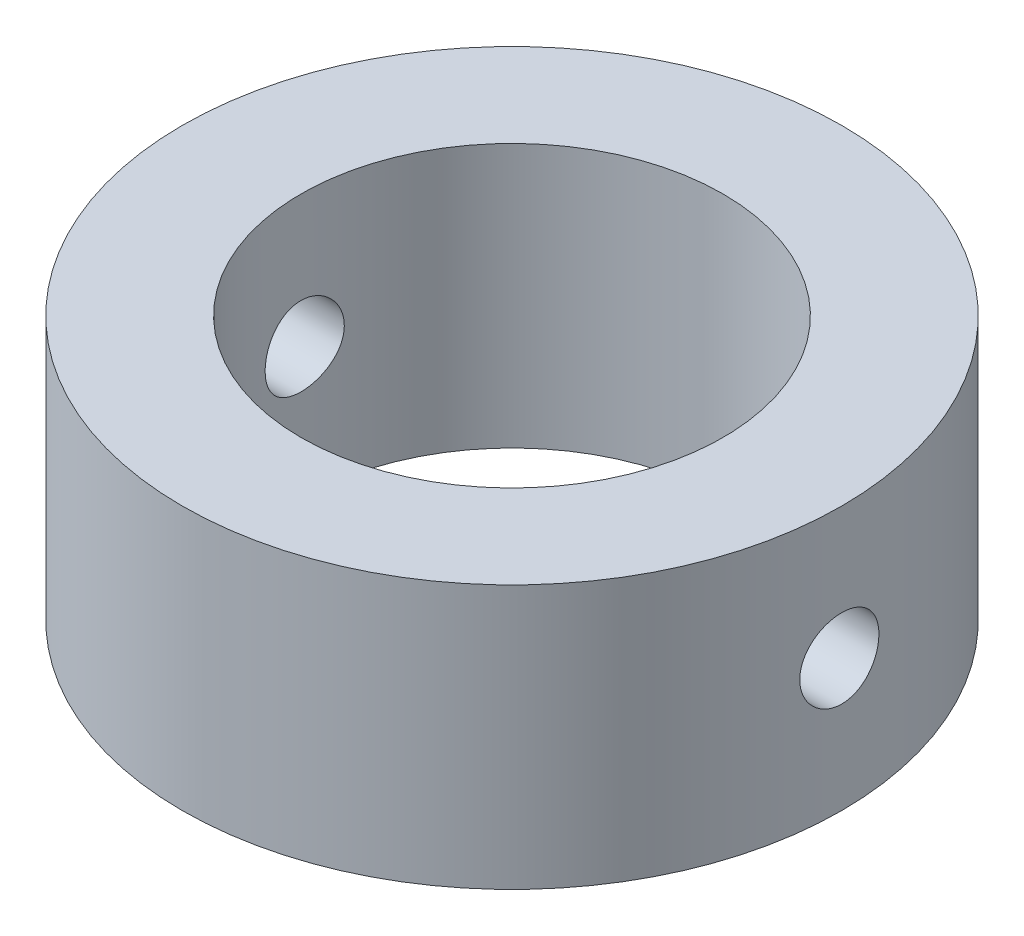
SolidWorks part; units mm, degrees
material "AISI 4130 Steel, normalized at 870C"
ref_plane "Front Plane" through (0, 0, 0) normal (0, 0, 1) x (1, 0, 0)
ref_plane "Top Plane" through (0, 0, 0) normal (0, 1, 0) x (1, 0, 0)
ref_plane "Right Plane" through (0, 0, 0) normal (1, 0, 0) x (0, 0, -1)
sketch "Sketch1" plane through (0, 0, 0) normal (0, 1, 0) x (1, 0, 0)
  circle A0 centre (0, 0) radius 12.5
  circle A1 centre (0, 0) radius 8
extrude "Boss-Extrude1" add sketch "Sketch1" along normal blind 10
sketch "Sketch2" plane through (0, 10, 0) normal (0, 1, 0) x (1, 0, 0)
  line L0 (0, 0) -> (-12.5, 0) construction
  circle A0 centre (0, 0) radius 12.5 construction
ref_plane "Plane1" through (-12.5, 0, 0) normal (-1, 0, 0) x (0, 0, 1)
sketch "Sketch3" plane through (-12.5, 0, 0) normal (-1, 0, 0) x (0, 0, 1)
  line L0 (8, 10) -> (-8, 10) construction
  line L1 (-12.5, 10) -> (-12.5, 0) construction
  circle A0 centre (0, 5) radius 1.5
  dimension "D1" = 5
  dimension "D2" = 12.5
extrude "Cut-Extrude1" cut sketch "Sketch3" against normal through all
